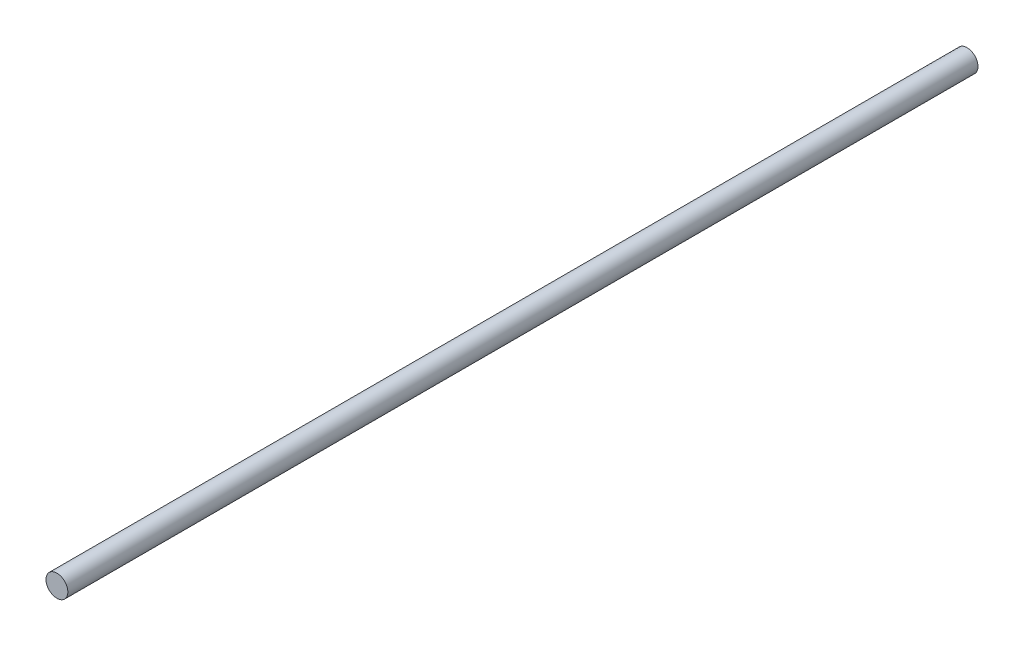
SolidWorks part; units mm, degrees
ref_plane "Front Plane" through (0, 0, 0) normal (0, 0, 1) x (1, 0, 0)
ref_plane "Top Plane" through (0, 0, 0) normal (0, 1, 0) x (1, 0, 0)
ref_plane "Right Plane" through (0, 0, 0) normal (1, 0, 0) x (0, 0, -1)
sketch "Sketch1" plane through (0, 0, 0) normal (0, 0, 1) x (1, 0, 0)
  circle A0 centre (0, 0) radius 3
extrude "Boss-Extrude1" add sketch "Sketch1" along normal blind 250
